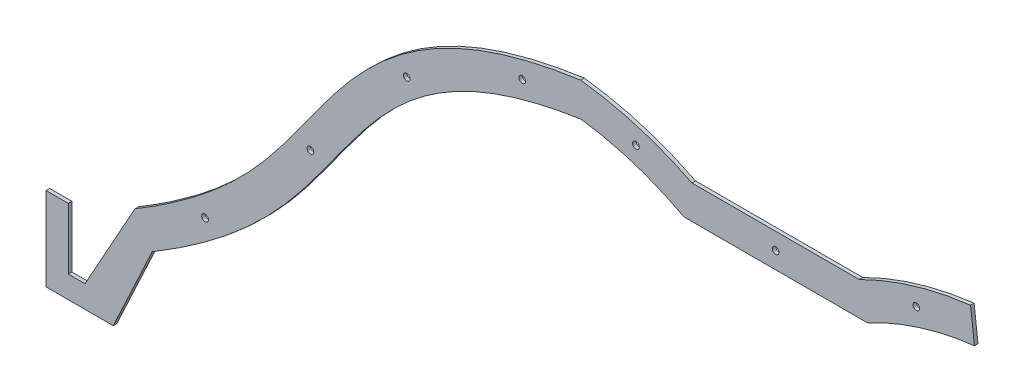
SolidWorks part; units mm, degrees
ref_plane "前视基准面" through (0, 0, 0) normal (0, 0, 1) x (1, 0, 0)
ref_plane "上视基准面" through (0, 0, 0) normal (0, 1, 0) x (1, 0, 0)
ref_plane "右视基准面" through (0, 0, 0) normal (1, 0, 0) x (0, 0, -1)
sketch "Sketch1" plane through (0, 0, 0) normal (0, 0, 1) x (1, 0, 0)
  line L0 (25, 170) -> (175, 170)
  line L1 (17.6763, 140) -> (182.3237, 140)
  line L2 (-475, -100) -> (-518.0311, -125.7444) construction
  line L3 (-518.0311, -125.7444) -> (-459.5978, -125.7444) construction
  line L4 (278.4889, 170.2036) -> (275, 200)
  line L5 (-467.2989, -112.8722) -> (-510.33, -138.6166) construction
  line L6 (21.3892, 155) -> (178.6108, 155) construction
  line L7 (-459.5978, -125.7444) -> (-494.5978, -200.7444)
  line L8 (-554.9628, -200.7444) -> (-494.5978, -200.7444)
  line L9 (-554.9628, -200.7444) -> (-554.9628, -125.7444)
  line L10 (-554.9628, -125.7444) -> (-534.9628, -125.7444)
  line L11 (-534.9628, -125.7444) -> (-534.9628, -180.7444)
  line L12 (-534.9628, -180.7444) -> (-519.9628, -180.7444)
  line L13 (-519.9628, -180.7444) -> (-475, -100)
  arc A0 (-75, 200) -> (25, 170) centre (-109.8893, -97.9643) cw
  arc A1 (175, 170) -> (275, 200) centre (309.8893, -97.9643) cw
  arc A2 (-74.6961, 169.7322) -> (17.6763, 140) centre (-109.8893, -97.9643) cw
  arc A3 (182.3237, 140) -> (278.4889, 170.2036) centre (309.8893, -97.9643) cw
  arc A4 (-74.8355, 184.8717) -> (21.3892, 155) centre (-109.8893, -97.9643) cw construction
  arc A5 (178.6108, 155) -> (276.7445, 185.1018) centre (309.8893, -97.9643) cw construction
  circle A6 centre (-412.1745, -75.7444) radius 3
  circle A7 centre (-317.6018, 24.2556) radius 3
  circle A8 centre (-231.0967, 124.2556) radius 3
  circle A9 centre (-127.4115, 174.2556) radius 3
  circle A10 centre (100, 155) radius 3
  circle A11 centre (226.3113, 174.5053) radius 3
  circle A12 centre (-25.3926, 174.2218) radius 3
  spline S0 degree 3 poles (-475, -100) (-419.5406, -66.8201) (-306.0139, 34.0368) (-257.6356, 174.2871) (-75, 200) knots 0 0 0 0 0.312224 1 1 1 1
  spline S1 degree 1 poles (-459.5978, -125.7444) (-74.6961, 169.7322) knots 0 0 1 1 construction
  spline S2 degree 3 poles (-459.5978, -125.7444) (-458.1678, -124.8889) (-455.301, -123.1604) (-449.693, -119.7258) (-442.8445, -115.4302) (-434.8975, -110.2806) (-424.643, -103.4106) (-412.4462, -94.8074) (-398.7329, -84.4255) (-385.8755, -73.9567) (-369.7872, -59.85) (-355.1526, -45.4768) (-341.7181, -30.7847) (-332.1609, -19.5812) (-323.1016, -8.241) (-311.6308, 6.8636) (-298.1175, 25.606) (-282.3957, 47.4316) (-266.3843, 68.251) (-249.3412, 87.8034) (-230.505, 105.9281) (-212.6012, 119.774) (-196.4574, 130.0489) (-183.3039, 137.3321) (-168.9692, 144.1624) (-153.318, 150.5001) (-136.2188, 156.2966) (-120.6588, 160.6298) (-107.3641, 163.768) (-96.9585, 165.9492) (-87.9034, 167.6182) (-80.4453, 168.8567) (-76.6048, 169.4489) (-74.6961, 169.7322) knots 0 0 0 0 0.007772 0.015544 0.031088 0.046632 0.062176 0.093264 0.124353 0.155441 0.186529 0.248705 0.279793 0.310882 0.34197 0.373058 0.435234 0.497411 0.559587 0.621763 0.68394 0.746116 0.777204 0.808292 0.83938 0.870469 0.901557 0.932645 0.948189 0.963733 0.979277 0.987049 0.994821 0.994821 0.994821 0.994821
  spline S3 degree 1 poles (-467.2989, -112.8722) (-74.8355, 184.8717) knots 0 0 1 1 construction
  spline S4 degree 3 poles (-467.2989, -112.8722) (-465.8947, -112.0321) (-463.0786, -110.3342) (-457.5762, -106.964) (-450.8636, -102.7531) (-443.0868, -97.7125) (-433.0675, -90.9979) (-423.8922, -84.5226) (-415.1487, -78.0342) (-409.9698, -74.0603) (-403.2446, -68.7575) (-394.6932, -61.7429) (-379.8313, -48.6964) (-362.184, -31.3406) (-343.2714, -9.8317) (-330.2359, 7.0702) (-320.4577, 20.3068) (-314.9027, 27.9731) (-305.7278, 40.7071) (-293.9593, 57.0194) (-277.6315, 78.2128) (-259.7555, 98.6534) (-244.7781, 112.9919) (-233.8839, 122.0718) (-226.3196, 128.0284) (-216.2598, 135.2631) (-203.2116, 143.4936) (-189.1356, 151.2095) (-173.8464, 158.4123) (-157.2257, 165.0566) (-142.3522, 170.0254) (-131.3386, 173.2066) (-124.74, 174.9742) (-117.7908, 176.7319) (-108.8769, 178.7966) (-98.0064, 181.0287) (-88.5695, 182.7287) (-80.809, 183.9859) (-76.8191, 184.5852) (-74.8355, 184.8717) knots 0 0 0 0 0.007793 0.015586 0.031172 0.046758 0.062344 0.093516 0.106904 0.12249 0.130283 0.155861 0.187033 0.249377 0.311721 0.374065 0.391607 0.422779 0.438365 0.498754 0.561098 0.623442 0.685786 0.700893 0.71648 0.748131 0.779303 0.810475 0.841647 0.872819 0.903991 0.918626 0.926419 0.935163 0.950749 0.966335 0.981921 0.989714 0.997507 0.997507 0.997507 0.997507 construction
  dimension "D5" = 300
  dimension "D8" = 300
  dimension "D14" = 50
  dimension "D18" = 6
  dimension "D19" = 6
  dimension "D20" = 6
  dimension "D21" = 6
  dimension "D22" = 6
  dimension "D23" = 6
  dimension "D24" = 6
  dimension "D1" = 120
  dimension "D2" = 100
  dimension "D3" = 400
  dimension "D4" = 300
  dimension "D6" = 100
  dimension "D7" = 30
  dimension "D9" = 100
  dimension "D10" = 30
  dimension "D11" = 150
  dimension "D13" = 15
  dimension "D15" = 150
  dimension "D16" = 250
  dimension "D17" = 300
  dimension "D25" = 412.1745
  dimension "D26" = 125.7444
  dimension "D27" = 75
  dimension "D28" = 20
  dimension "D29" = 35
  dimension "D12" = 30
extrude "Boss-Extrude1" add sketch "Sketch1" along normal blind 3.175
